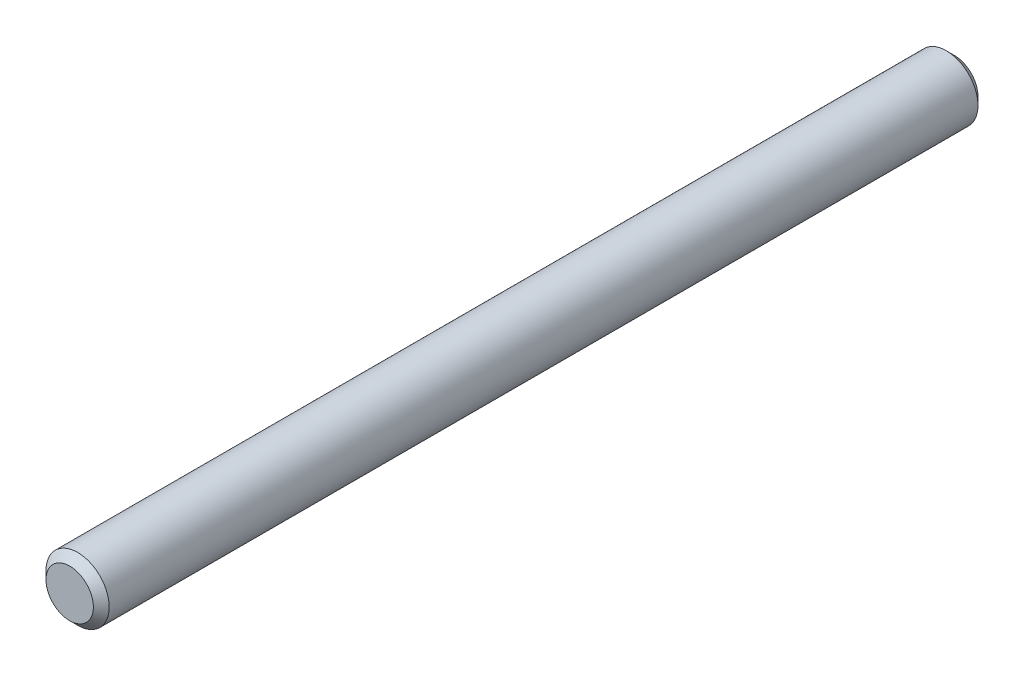
SolidWorks part; units mm, degrees
ref_plane "Plan de face" through (0, 0, 0) normal (0, 0, 1) x (1, 0, 0)
ref_plane "Plan de dessus" through (0, 0, 0) normal (0, 1, 0) x (1, 0, 0)
ref_plane "Plan de droite" through (0, 0, 0) normal (1, 0, 0) x (0, 0, -1)
ref_plane "Plan1" through (0, 0, 0) normal (0, -1, 0) x (1, 0, 0)
sketch "Esquisse1" plane through (0, 0, 0) normal (0, -1, 0) x (1, 0, 0)
  line L0 (0.75, 14) -> (0, 14)
  line L1 (0, 14) -> (0, -14)
  line L2 (0, -14) -> (0.75, -14)
  line L3 (0.75, -14) -> (1, -13.75)
  line L4 (1, -13.75) -> (1, 13.75)
  line L5 (1, 13.75) -> (0.75, 14)
  line L6 (0, 14) -> (0, -14) construction
  line L7 (0, 18.9373) -> (0, -18.5683) construction
  point P4 (1, -14)
  point P5 (1, 14)
  dimension "D1" = 28
  dimension "D2" = 2
revolve "Révolution1" add sketch "Esquisse1" angle 360 about L6
